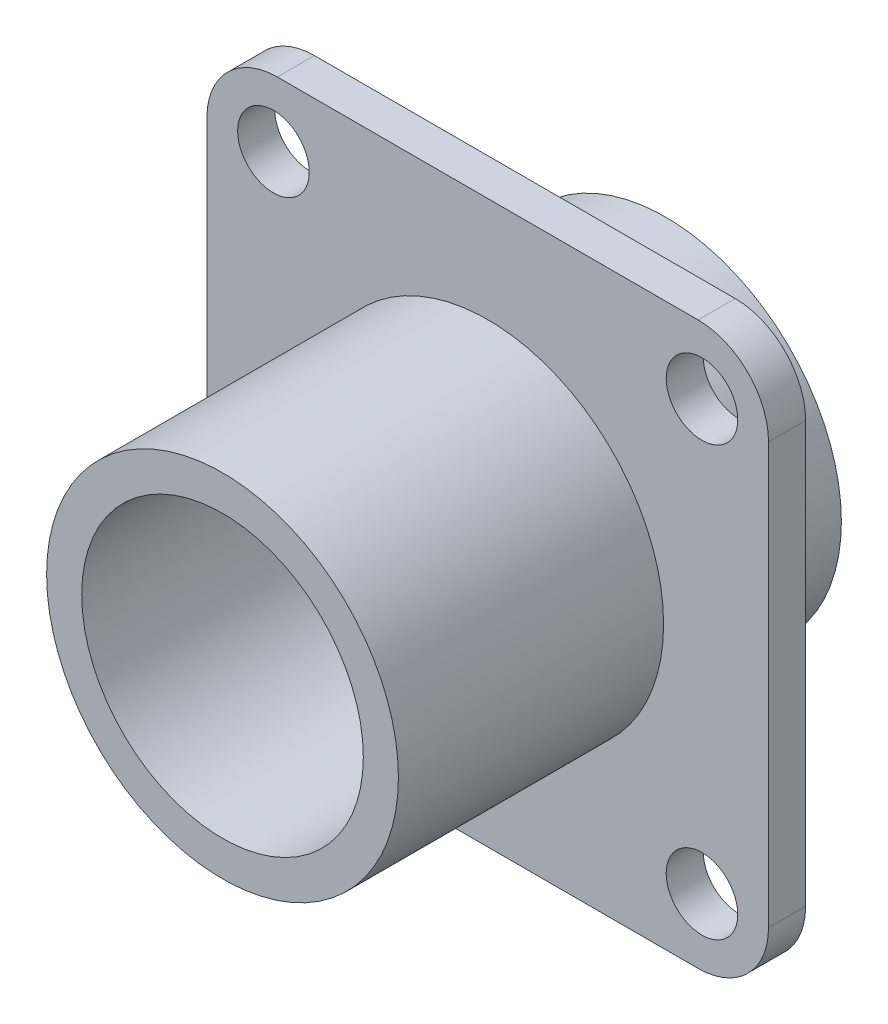
SolidWorks part; units mm, degrees
ref_plane "Спереди" through (0, 0, 0) normal (0, 0, 1) x (1, 0, 0)
ref_plane "Сверху" through (0, 0, 0) normal (0, 1, 0) x (1, 0, 0)
ref_plane "Справа" through (0, 0, 0) normal (1, 0, 0) x (0, 0, -1)
ref_plane "Плоскость4" through (0, 0, 0) normal (0, 0, -1) x (-1, 0, 0)
sketch "Эскиз1" plane through (0, 0, 0) normal (0, 0, -1) x (-1, 0, 0)
  line L0 (11.965, -11.965) -> (11.965, 11.965)
  line L1 (11.965, 11.965) -> (-11.965, 11.965)
  line L2 (-11.965, 11.965) -> (-11.965, -11.965)
  line L3 (-11.965, -11.965) -> (11.965, -11.965)
extrude "Бобышка-Вытянуть1" add sketch "Эскиз1" against normal blind 1.58
sketch "Эскиз2" plane through (0, 0, 0) normal (0, 1, 0) x (1, 0, 0)
  line L0 (7.495, -1.58) -> (0, -1.58)
  line L1 (0, -1.58) -> (0, -12.88)
  line L2 (0, -12.88) -> (7.495, -12.88)
  line L3 (7.495, -12.88) -> (7.495, -1.58)
  line L4 (0, -1.58) -> (0, -12.88) construction
revolve "Повернуть1" add sketch "Эскиз2" angle 360 about L4
ref_plane "Плоскость5" through (0, 0, 0) normal (0, -1, 0) x (1, 0, 0)
sketch "Эскиз3" plane through (0, 0, 0) normal (0, -1, 0) x (1, 0, 0)
  line L0 (7.49, 0) -> (0, 0)
  line L1 (0, 0) -> (0, -7.44)
  line L2 (0, -7.44) -> (7.49, -7.44)
  line L3 (7.49, -7.44) -> (7.49, 0)
  line L4 (0, 0) -> (0, -7.44) construction
revolve "Повернуть2" add sketch "Эскиз3" angle 360 about L4
hole_wizard "Отверстие с зазором M2.51" positions "Эскиз5" profile "Эскиз4" hole size "M2.5" standard "Ansi Metric"
sketch "Эскиз5" plane through (0, 0, 0) normal (0, 0, -1) x (-1, 0, 0)
  point P0 (9.13, -9.13)
  point P1 (9.13, 9.13)
  point P2 (-9.13, 9.13)
  point P3 (-9.13, -9.13)
sketch "Эскиз4" plane through (-9.13, -9.13, 0) normal (1, 0, 0) x (0, 1, 0)
  line L0 (0, 0) -> (0, 12.88)
  line L1 (0, 12.88) -> (1.525, 12.88)
  line L2 (1.525, 12.88) -> (1.525, 0)
  line L5 (1.525, 0) -> (0, 0)
  line L11 (0, -6.35) -> (0, 107.95) construction
  dimension "Диаметр сквозного отверстия" = 3.05
  dimension "Глубина сквозного отверстия" = 12.88
hole_wizard "Диаметр отверстия Ø12.0 (12)1" positions "Эскиз7" profile "Эскиз6" hole size "Ø12.0" standard "Ansi Metric"
sketch "Эскиз7" plane through (0, 0, 12.88) normal (0, 0, 1) x (1, 0, 0)
  point P0 (0, 0)
sketch "Эскиз6" plane through (0, 0, 12.88) normal (1, 0, 0) x (0, -1, 0)
  line L0 (0, 0) -> (0, 10)
  line L1 (0, 10) -> (6, 10)
  line L2 (6, 10) -> (6, 0)
  line L5 (6, 0) -> (0, 0)
  line L10 (0, 10) -> (-6, 10) construction
  line L11 (0, -6.35) -> (0, 107.95) construction
  dimension "Диаметр отверстия" = 12
  dimension "Глубина отверстия" = 10
  dimension "Угол заточки сверла" = 180
fillet "Скругление1" radius 3 4 edges at (-11.965, 11.965, 0.79) (11.965, 11.965, 0.79) (-11.965, -11.965, 0.79) (11.965, -11.965, 0.79)
sketch "Эскиз8" plane through (0, 0, 2.88) normal (0, 0, 1) x (1, 0, 0)
  circle A0 centre (0, 0) radius 6
extrude "Вырез-Вытянуть1" cut sketch "Эскиз8" against normal blind 15
sketch "Эскиз9" plane through (0, 0, -7.44) normal (0, 0, -1) x (-1, 0, 0)
  circle A0 centre (0, 0) radius 6
  circle A1 centre (0, 0) radius 7.49
extrude "Вырез-Вытянуть3" cut sketch "Эскиз9" against normal blind 1.44 contours A0
